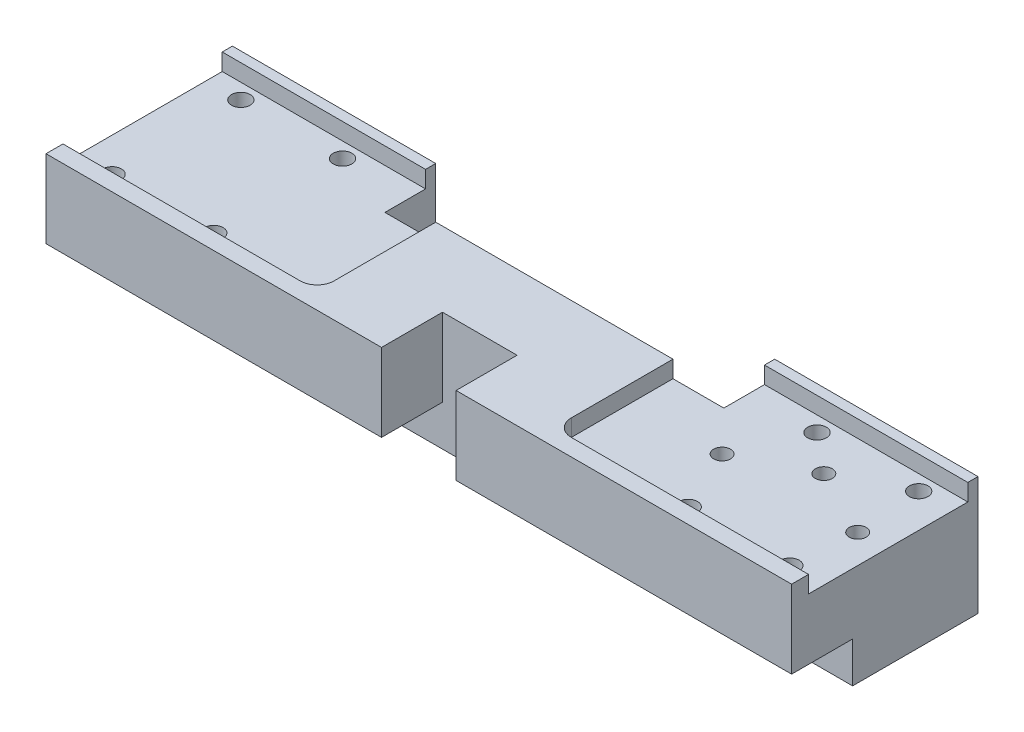
SolidWorks part; units mm, degrees
ref_plane "Front Plane" through (0, 0, 0) normal (0, 0, 1) x (1, 0, 0)
ref_plane "Top Plane" through (0, 0, 0) normal (0, 1, 0) x (1, 0, 0)
ref_plane "Right Plane" through (0, 0, 0) normal (1, 0, 0) x (0, 0, -1)
sketch "Sketch1" plane through (0, 0, 0) normal (0, 1, 0) x (1, 0, 0)
  line L1 (-110, 27.5) -> (110, 27.5)
  line L2 (-110, 27.5) -> (-110, -27.5)
  line L3 (-110, -27.5) -> (110, -27.5)
  line L4 (110, 27.5) -> (110, -27.5)
  line L5 (-110, 27.5) -> (110, -27.5) construction
  line L6 (-110, -27.5) -> (110, 27.5) construction
  point P0 (0, 0)
  dimension "D1" = 220
  dimension "D2" = 55
extrude "Boss-Extrude1" add sketch "Sketch1" along normal mid plane 35
sketch "Sketch2" plane through (0, 17.5, 0) normal (0, 1, 0) x (1, 0, 0)
  line L0 (110, 27.5) -> (-110, 27.5) construction
  line L1 (-115, 24.5) -> (-35, 24.5)
  line L2 (-115, 24.5) -> (-115, -22.5)
  line L3 (-115, -22.5) -> (-35, -22.5)
  line L4 (-35, 24.5) -> (-35, -22.5)
  line L5 (-110, 27.5) -> (-110, -27.5) construction
  dimension "D1" = 3
  dimension "D2" = 47
  dimension "D3" = 5
  dimension "D4" = 80
extrude "Cut-Extrude1" cut sketch "Sketch2" against normal blind 5
mirror "Mirror1" about plane through (0, 0, 0) normal (1, 0, 0) of "Cut-Extrude1"
hole_wizard "CBORE for M5 Hex Socket Head Cap Screw1" positions "Sketch3" profile "Sketch4" counterbore size "M5" standard "ISO" end condition through all
sketch "Sketch3" plane through (0, -17.5, 0) normal (0, -1, 0) x (-1, 0, 0)
  line L1 (-110, 27.5) -> (110, 27.5) construction
  line L2 (-110, -27.5) -> (-110, 27.5) construction
  line L3 (110, 27.5) -> (110, -27.5) construction
  point P0 (-100, 20)
  point P2 (-70, 20)
  point P4 (-70, -18)
  point P6 (-100, -18)
  point P8 (70, 20)
  point P10 (100, 20)
  point P12 (100, -18)
  point P14 (70, -18)
  dimension "D1" = 38
  dimension "D2" = 30
  dimension "D3" = 30
  dimension "D4" = 7.5
  dimension "D5" = 10
  dimension "D6" = 10
sketch "Sketch4" plane through (100, -17.5, -20) normal (1, 0, 0) x (0, 0, -1)
  line L0 (0, 0) -> (0, 35)
  line L1 (0, 35) -> (2.75, 35)
  line L3 (2.75, 35) -> (2.75, 24)
  line L4 (2.75, 24) -> (5, 24)
  line L5 (5, 24) -> (5, 0)
  line L7 (5, 0) -> (0, 0)
  line L11 (0, -6.35) -> (0, 107.95) construction
  dimension "Thru Hole Dia." = 5.5
  dimension "Thru Hole Depth" = 35
  dimension "C'Bore Dia." = 10
  dimension "C'Bore Depth" = 24
sketch "Sketch10" plane through (-110, 0, 0) normal (-1, 0, 0) x (0, 0, 1)
  line L1 (27.5, -17.5) -> (9.5, -17.5)
  line L2 (27.5, -17.5) -> (27.5, -5.5)
  line L3 (27.5, -5.5) -> (9.5, -5.5)
  line L4 (9.5, -17.5) -> (9.5, -5.5)
  dimension "D1" = 18
  dimension "D2" = 12
extrude "Cut-Extrude4" cut sketch "Sketch10" against normal through all
sketch "Sketch5" plane through (0, -17.5, 0) normal (0, -1, 0) x (1, 0, 0)
  line L0 (110, -27.5) -> (-110, -27.5) construction
  line L1 (50, -92.5) -> (-50, -92.5)
  line L2 (50, -92.5) -> (50, -12.5)
  line L3 (50, -12.5) -> (-50, -12.5)
  line L4 (-50, -92.5) -> (-50, -12.5)
  dimension "D1" = 50
  dimension "D2" = 100
  dimension "D3" = 15
  dimension "D4" = 80
extrude "Cut-Extrude2" cut sketch "Sketch5" against normal through all
sketch "Sketch6" plane through (0, -17.5, 0) normal (0, -1, 0) x (1, 0, 0)
  line L0 (110, 27.5) -> (-110, 27.5) construction
  line L1 (-11, 53.6803) -> (11, 53.6803)
  line L2 (-11, 53.6803) -> (-11, 9.5)
  line L3 (-11, 9.5) -> (11, 9.5)
  line L4 (11, 53.6803) -> (11, 9.5)
  point P7 (0, 9.5)
  dimension "D1" = 18
  dimension "D2" = 22
extrude "Cut-Extrude3" cut sketch "Sketch6" against normal through all
fillet "Fillet1" radius 5 2 edges at (35, 15, 22.5) (-35, 15, 22.5)
hole_wizard "M5 Tapped Hole1" positions "Sketch7" profile "Sketch8" tap size "M5" standard "ISO"
sketch "Sketch7" plane through (0, 0, -12.5) normal (0, 0, -1) x (-1, 0, 0)
  point P0 (-17, 12)
  point P2 (17, 12)
  point P4 (17, -12)
  point P6 (-17, -12)
  dimension "D1" = 17
  dimension "D2" = 34
  dimension "D3" = 24
  dimension "D4" = 12
sketch "Sketch8" plane through (17, 12, -12.5) normal (1, 0, 0) x (0, 1, 0)
  line L0 (0, 0) -> (0, 15.2618)
  line L1 (0, 15.2618) -> (2.1, 14)
  line L2 (2.1, 14) -> (2.1, 0)
  line L5 (2.1, 0) -> (0, 0)
  line L10 (0, 15.2618) -> (-2.1, 14) construction
  line L11 (0, -6.35) -> (0, 107.95) construction
  dimension "Tap Drill Dia." = 4.2
  dimension "Tap Drill Depth" = 14
  dimension "Drill Angle" = 118
cosmetic thread "Hole Thread1" parameters "D1"=10, "D2"=5
cosmetic thread "Hole Thread2" parameters "D1"=10, "D2"=5
cosmetic thread "Hole Thread3" parameters "D1"=10, "D2"=5
cosmetic thread "Hole Thread4" parameters "D1"=10, "D2"=5
hole_wizard "M6 Tapped Hole1" positions "Sketch11" profile "Sketch12" tap size "M6" standard "ISO"
sketch "Sketch11" plane through (0, -17.5, 0) normal (0, -1, 0) x (-1, 0, 0)
  line L0 (-110, -9.5) -> (-110, 27.5) construction
  line L1 (-110, 27.5) -> (-50, 27.5) construction
  point P0 (-101.5, 0.5)
  point P2 (-81.5, 10.5)
  point P4 (-61.5, 0.5)
  dimension "D1" = 10
  dimension "D2" = 20
  dimension "D3" = 20
  dimension "D4" = 8.5
  dimension "D5" = 27
cosmetic thread "Hole Thread5" parameters "D1"=30, "D2"=6
cosmetic thread "Hole Thread6" parameters "D1"=30, "D2"=6
cosmetic thread "Hole Thread7" parameters "D1"=30, "D2"=6
sketch "Sketch12" plane through (101.5, -17.5, -0.5) normal (1, 0, 0) x (0, 0, -1)
  line L0 (0, 0) -> (0, 36.5022)
  line L1 (0, 36.5022) -> (2.5, 35)
  line L2 (2.5, 35) -> (2.5, 0)
  line L5 (2.5, 0) -> (0, 0)
  line L10 (0, 36.5022) -> (-2.5, 35) construction
  line L11 (0, -6.35) -> (0, 107.95) construction
  dimension "Tap Drill Dia." = 5
  dimension "Tap Drill Depth" = 35
  dimension "Drill Angle" = 118
hole_wizard "Ø6.0mm Dowel Hole1" positions "Sketch13" profile "Sketch14" hole size "Ø6.0" standard "JIS"
sketch "Sketch13" plane through (0, -17.5, 0) normal (0, -1, 0) x (-1, 0, 0)
  circle A0 centre (-81.5, 10.5) radius 2.5 construction
  circle A1 centre (-101.5, 0.5) radius 2.5 construction
  point P0 (-101.5, 10.5)
  point P2 (-61.5, 10.5)
  dimension "D1" = 20
  dimension "D2" = 20
  dimension "D3" = 10
sketch "Sketch14" plane through (101.5, -17.5, -10.5) normal (1, 0, 0) x (0, 0, -1)
  line L0 (0, 0) -> (0, 21.8026)
  line L1 (0, 21.8026) -> (3, 20)
  line L2 (3, 20) -> (3, 0)
  line L5 (3, 0) -> (0, 0)
  line L10 (0, 21.8026) -> (-3, 20) construction
  line L11 (0, -6.35) -> (0, 107.95) construction
  dimension "Hole Dia." = 6
  dimension "Hole Depth" = 20
  dimension "Drill Angle" = 118
